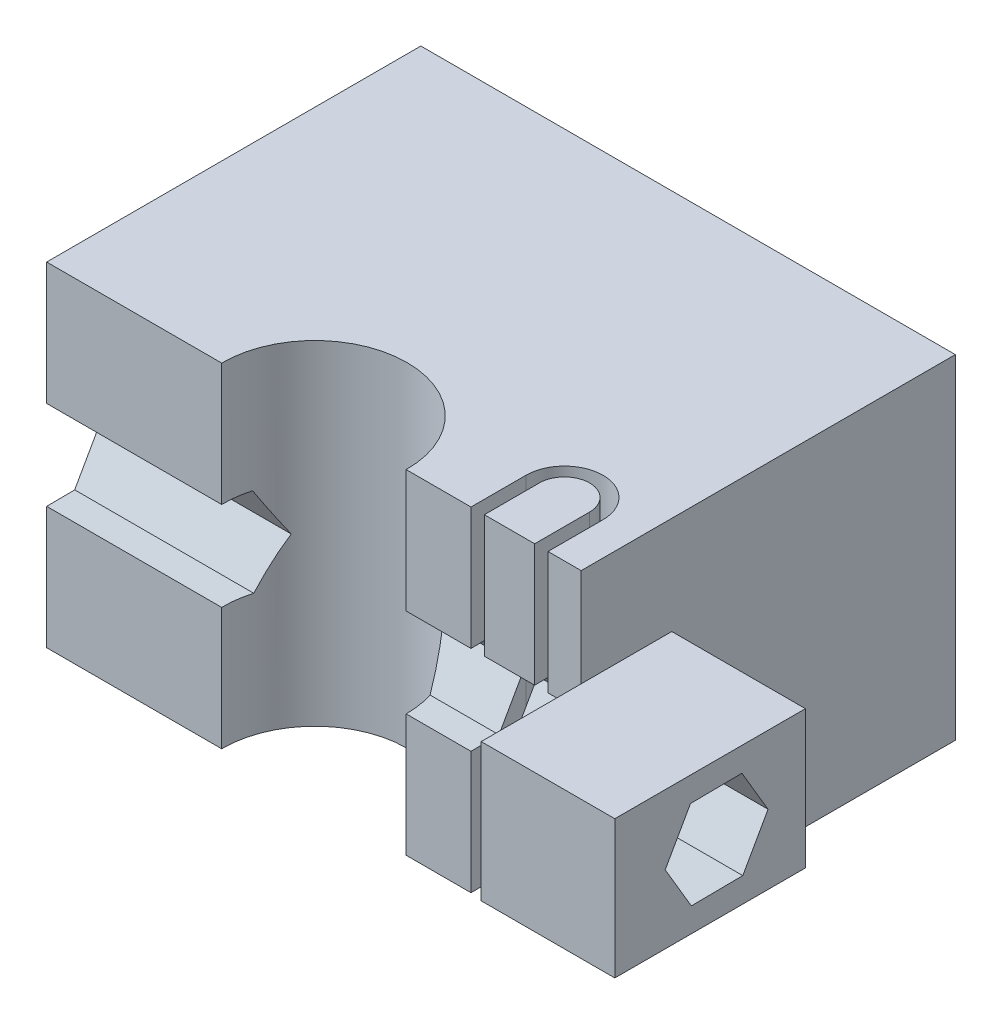
SolidWorks part; units mm, degrees
ref_plane "Front Plane" through (0, 0, 0) normal (0, 0, 1) x (1, 0, 0)
ref_plane "Top Plane" through (0, 0, 0) normal (0, 1, 0) x (1, 0, 0)
ref_plane "Right Plane" through (0, 0, 0) normal (1, 0, 0) x (0, 0, -1)
sketch "Sketch1" plane through (0, 0, 0) normal (0, 0, 1) x (1, 0, 0)
  line L0 (-69.6651, 0) -> (67.3684, 0) construction
  line L1 (0, 59.2344) -> (0, -45.2632) construction
  line L3 (-40, 25) -> (40, 25)
  line L4 (-40, 25) -> (-40, -25)
  line L5 (-40, -25) -> (40, -25)
  line L6 (40, 25) -> (40, -25)
  line L7 (-40, 25) -> (40, -25) construction
  line L8 (-40, -25) -> (40, 25) construction
  point P5 (0, 0)
  dimension "D1" = 80
  dimension "D2" = 50
extrude "Boss-Extrude1" add sketch "Sketch1" along normal mid plane 56
sketch "Sketch4" plane through (40, 0, 0) normal (1, 0, 0) x (0, 0, -1)
  line L0 (-28, -25) -> (-28, 25) construction
  line L6 (-14.439, -10.3237) -> (-42.9655, -10.3237)
  line L7 (-28, 25) -> (28, 25) construction
  line L8 (-14.439, -10.3237) -> (-14.439, 10.3237)
  line L9 (-14.439, 10.3237) -> (-42.9655, 10.3237)
  line L10 (-42.9655, -10.3237) -> (-42.9655, 10.3237)
  line L11 (-14.439, -10.3237) -> (-42.9655, 10.3237) construction
  line L12 (-14.439, 10.3237) -> (-42.9655, -10.3237) construction
  point P0 (-28, 25)
  point P1 (-28.7022, 0)
extrude "Boss-Extrude2" add sketch "Sketch4" along normal blind 20
sketch "Sketch5" plane through (0, -25, 0) normal (0, -1, 0) x (-1, 0, 0)
  circle A0 centre (0, -27.8625) radius 13.805
extrude "Cut-Extrude1" cut sketch "Sketch5" against normal blind 101
sketch "Sketch6" plane through (0, 25, 0) normal (0, 1, 0) x (1, 0, 0)
  line L0 (29.2732, -19.771) -> (29.2732, -42.6878) construction
  line L1 (33.0392, -19.771) -> (33.0392, -42.6878)
  line L2 (25.5072, -19.771) -> (25.5072, -42.6878)
  arc A0 (33.0392, -19.771) -> (25.5072, -19.771) centre (29.2732, -19.771) ccw
  arc A1 (25.5072, -42.6878) -> (33.0392, -42.6878) centre (29.2732, -42.6878) ccw
  point P2 (29.2732, -31.2294)
extrude "Cut-Extrude-Thin1" cut sketch "Sketch6" against normal blind 101 thin thin type one direction wall 2
sketch "Sketch8" plane through (60, 0, 0) normal (1, 0, 0) x (0, 0, -1)
  line L1 (-23.9428, 6.7046) -> (-31.6403, 6.6277)
  line L2 (-31.6403, 6.6277) -> (-35.4224, -0.0769)
  line L3 (-35.4224, -0.0769) -> (-31.507, -6.7046)
  line L4 (-31.507, -6.7046) -> (-23.8096, -6.6277)
  line L5 (-23.8096, -6.6277) -> (-20.0275, 0.0769)
  line L6 (-20.0275, 0.0769) -> (-23.9428, 6.7046)
  circle A0 centre (-27.7249, 0) radius 6.6665 construction
extrude "Cut-Extrude2" cut sketch "Sketch8" against normal blind 186
